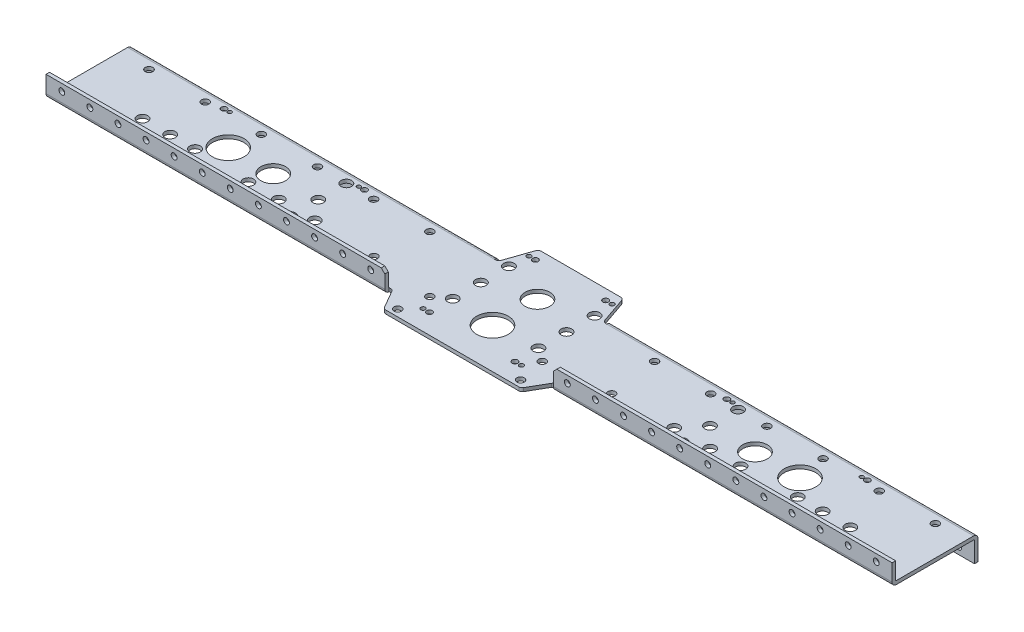
SolidWorks part; units mm, degrees
ref_plane "Front Plane" through (0, 0, 0) normal (0, 0, 1) x (1, 0, 0)
ref_plane "Top Plane" through (0, 0, 0) normal (0, 1, 0) x (1, 0, 0)
ref_plane "Right Plane" through (0, 0, 0) normal (1, 0, 0) x (0, 0, -1)
ref_plane "Plane1" through (0, 3.175, 0) normal (0, 1, 0) x (1, 0, 0)
sketch "Sketch1" plane through (0, 3.175, 0) normal (0, 1, 0) x (1, 0, 0)
  line L0 (457.2, 73.787) -> (457.2, -3.937)
  line L1 (457.2, -3.937) -> (812.8, -3.937)
  line L2 (812.8, -3.937) -> (812.8, 73.787)
  line L3 (812.8, 73.787) -> (457.2, 73.787)
extrude "Boss-Extrude1" add sketch "Sketch1" against normal blind 22.225
sketch "Sketch2" plane through (812.8, 0, 0) normal (1, 0, 0) x (0, 0, -1)
  line L0 (70.612, -19.05) -> (70.612, 0)
  line L1 (70.612, 0) -> (-3.937, 0)
  line L2 (-3.937, 0) -> (-3.937, -19.05)
  line L3 (-3.937, -19.05) -> (70.612, -19.05)
extrude "Cut-Extrude1" cut sketch "Sketch2" against normal through all
sketch "Sketch3" plane through (0, 0, 0) normal (0, -1, 0) x (1, 0, 0)
  line L0 (457.2, 0) -> (482.6, 0)
  line L1 (482.6, 0) -> (482.6, 3.937)
  line L2 (482.6, 3.937) -> (457.2, 3.937)
  line L3 (457.2, 3.937) -> (457.2, 0)
extrude "Cut-Extrude2" cut sketch "Sketch3" against normal through all
sketch "Sketch4" plane through (0, 3.175, 0) normal (0, 1, 0) x (-1, 0, 0)
  line L0 (-812.8, 3.937) -> (-482.6, 3.937)
  line L1 (-482.6, 3.937) -> (-482.6, 0.762)
  line L2 (-482.6, 0.762) -> (-812.8, 0.762)
  line L3 (-812.8, 0.762) -> (-812.8, 3.937)
extrude "Boss-Extrude2" add sketch "Sketch4" along normal blind 15.875
sketch "Sketch5" plane through (457.2, 0, 0) normal (-1, 0, 0) x (0, 0, 1)
  line L0 (0, 3.175) -> (0, 0)
  line L1 (0, 0) -> (-69.85, 0)
  line L2 (-69.85, 0) -> (-69.85, 3.175)
  line L3 (-69.85, 3.175) -> (0, 3.175)
extrude "Boss-Extrude3" add sketch "Sketch5" along normal blind 457.2
sketch "Sketch6" plane through (0, 0, 0) normal (0, 0, 1) x (1, 0, 0)
  line L0 (330.2, 3.175) -> (330.2, 0)
  line L1 (330.2, 0) -> (0, 0)
  line L2 (0, 0) -> (0, 3.175)
  line L3 (0, 3.175) -> (330.2, 3.175)
extrude "Boss-Extrude4" add sketch "Sketch6" along normal blind 3.937
sketch "Sketch7" plane through (0, 3.175, 0) normal (0, 1, 0) x (-1, 0, 0)
  line L0 (-330.2, 3.937) -> (0, 3.937)
  line L1 (0, 3.937) -> (0, 0.762)
  line L2 (0, 0.762) -> (-330.2, 0.762)
  line L3 (-330.2, 0.762) -> (-330.2, 3.937)
extrude "Boss-Extrude5" add sketch "Sketch7" along normal blind 15.875
sketch "Sketch8" plane through (0, 0, -69.85) normal (0, 0, -1) x (-1, 0, 0)
  line L0 (-355.6, 0) -> (-355.6, 3.175)
  line L1 (-355.6, 3.175) -> (0, 3.175)
  line L2 (0, 3.175) -> (0, 0)
  line L3 (0, 0) -> (-355.6, 0)
extrude "Boss-Extrude6" add sketch "Sketch8" along normal blind 3.937
sketch "Sketch9" plane through (0, 0, 0) normal (0, -1, 0) x (1, 0, 0)
  line L0 (0, -70.612) -> (355.6, -70.612)
  line L1 (355.6, -70.612) -> (355.6, -73.787)
  line L2 (355.6, -73.787) -> (0, -73.787)
  line L3 (0, -73.787) -> (0, -70.612)
extrude "Boss-Extrude7" add sketch "Sketch9" along normal blind 19.05
sketch "Sketch10" plane through (0, 0, 0) normal (0, 0, 1) x (1, 0, 0)
  line L0 (344.3735, 3.175) -> (468.4265, 3.175)
  line L1 (468.4265, 3.175) -> (468.4265, 0)
  line L2 (468.4265, 0) -> (344.3735, 0)
  line L3 (344.3735, 0) -> (344.3735, 3.175)
extrude "Boss-Extrude8" add sketch "Sketch10" along normal blind 19.05
sketch "Sketch11" plane through (0, 0, -69.85) normal (0, 0, -1) x (-1, 0, 0)
  line L0 (-444.5794, 3.175) -> (-368.2206, 3.175)
  line L1 (-368.2206, 3.175) -> (-368.2206, 0)
  line L2 (-368.2206, 0) -> (-444.5794, 0)
  line L3 (-444.5794, 0) -> (-444.5794, 3.175)
extrude "Boss-Extrude9" add sketch "Sketch11" along normal blind 27.432
draft "Draft1" type of draft neutral plane draft angle 30 faces to draft 2 face at (344.3735, 1.5875, 9.525) face at (468.4265, 1.5875, 9.525) neutral plane through (0, 0, 19.05) neutral plane normal (0, 0, 1) parameters "D1"=30
draft "Draft2" type of draft neutral plane draft angle 19 faces to draft 2 face at (368.2206, 1.5875, -83.566) face at (444.5794, 1.5875, -83.566) neutral plane through (0, 0, -97.282) neutral plane normal (0, 0, -1) parameters "D1"=19
hole_wizard "#6 Clearance Hole1" positions "Sketch13" profile "Sketch12" hole size "#6" standard "ANSI Inch"
sketch "Sketch13" plane through (0, 0, 0) normal (0, -1, 0) x (-1, 0, 0)
  point P0 (-450.8881, -1.0389)
  point P1 (-361.9119, -1.0389)
  point P2 (-368.808, 87.8535)
  point P3 (-443.992, 87.8535)
sketch "Sketch12" plane through (450.8881, 0, 1.0389) normal (1, 0, 0) x (0, 0, -1)
  line L0 (0, 0) -> (0, 19.05)
  line L1 (0, 19.05) -> (2.032, 19.05)
  line L2 (2.032, 19.05) -> (2.032, 0)
  line L5 (2.032, 0) -> (0, 0)
  line L11 (0, -6.35) -> (0, 107.95) construction
  dimension "Thru Hole Dia." = 4.064
  dimension "Thru Hole Depth" = 19.05
hole_wizard "Hole1" positions "Sketch15" profile "Sketch14" legacy
sketch "Sketch15" plane through (0, 0, 0) normal (0, -1, 0) x (-1, 0, 0)
  point P0 (-147.8292, 36.83)
  point P1 (-406.4, 17.272)
  point P2 (-664.9708, 36.83)
sketch "Sketch14" plane through (147.8292, 0, -36.83) normal (1, 0, 0) x (0, 0, -1)
  line L0 (0, 0) -> (0, 19.05)
  line L1 (0, 19.05) -> (14.2875, 19.05)
  line L2 (14.2875, 19.05) -> (14.2875, 0)
  line L3 (14.2875, 0) -> (0, 0)
  line L4 (0, 110) -> (0, -10) construction
  dimension "Diameter" = 28.575
  dimension "Depth" = 19.05
hole_wizard "7/8 (0.875) Diameter Hole1" positions "Sketch17" profile "Sketch16" hole size "7/8" standard "ANSI Inch"
sketch "Sketch17" plane through (0, 0, 0) normal (0, -1, 0) x (-1, 0, 0)
  point P0 (-188.5454, 36.83)
  point P1 (-406.4, 57.9628)
  point P2 (-624.2546, 36.83)
sketch "Sketch16" plane through (188.5454, 0, -36.83) normal (1, 0, 0) x (0, 0, -1)
  line L0 (0, 0) -> (0, 19.05)
  line L1 (0, 19.05) -> (11.1125, 19.05)
  line L2 (11.1125, 19.05) -> (11.1125, 0)
  line L5 (11.1125, 0) -> (0, 0)
  line L11 (0, -6.35) -> (0, 107.95) construction
  dimension "Thru Hole Dia." = 22.225
  dimension "Thru Hole Depth" = 19.05
hole_wizard "3/8 (0.375) Diameter Hole1" positions "Sketch19" profile "Sketch18" hole size "3/8" standard "ANSI Inch"
sketch "Sketch19" plane through (0, 0, 0) normal (0, -1, 0) x (-1, 0, 0)
  point P0 (-229.2616, 11.43)
  point P1 (-229.2616, 62.23)
  point P2 (-229.2616, 36.83)
  point P3 (-367.6757, 70.866)
  point P4 (-367.6757, 20.066)
  point P5 (-445.1243, 20.066)
  point P6 (-445.1243, 70.866)
  point P7 (-367.6757, 45.466)
  point P8 (-445.1243, 45.466)
  point P9 (-628.9477, 19.05)
  point P10 (-601.4385, 19.05)
  point P11 (-568.9249, 19.05)
  point P12 (-243.8751, 19.05)
  point P13 (-211.3615, 19.05)
  point P14 (-183.8523, 19.05)
  point P15 (-678.9442, 20.828)
  point P16 (-701.4504, 20.828)
  point P17 (-726.4609, 20.828)
  point P18 (-133.8558, 20.828)
  point P19 (-111.3496, 20.828)
  point P20 (-86.3391, 20.828)
  point P21 (-583.5384, 62.23)
  point P22 (-583.5384, 36.83)
  point P23 (-583.5384, 11.43)
sketch "Sketch18" plane through (229.2616, 0, -11.43) normal (1, 0, 0) x (0, 0, -1)
  line L0 (0, 0) -> (0, 19.05)
  line L1 (0, 19.05) -> (4.7625, 19.05)
  line L2 (4.7625, 19.05) -> (4.7625, 0)
  line L5 (4.7625, 0) -> (0, 0)
  line L11 (0, -6.35) -> (0, 107.95) construction
  dimension "Thru Hole Dia." = 9.525
  dimension "Thru Hole Depth" = 19.05
hole_wizard "#5 Clearance Hole1" positions "Sketch21" profile "Sketch20" hole size "#5" standard "ANSI Inch"
sketch "Sketch21" plane through (0, 0, 0) normal (0, -1, 0) x (-1, 0, 0)
  point P0 (-237.4404, 65.405)
  point P1 (-237.4404, 8.255)
  point P2 (-120.6004, 8.255)
  point P3 (-120.6004, 65.405)
  point P4 (-575.3596, 65.405)
  point P5 (-575.3596, 8.255)
  point P6 (-692.1996, 65.405)
  point P7 (-692.1996, 8.255)
sketch "Sketch20" plane through (237.4404, 0, -65.405) normal (1, 0, 0) x (0, 0, -1)
  line L0 (0, 0) -> (0, 19.05)
  line L1 (0, 19.05) -> (1.7859, 19.05)
  line L2 (1.7859, 19.05) -> (1.7859, 0)
  line L5 (1.7859, 0) -> (0, 0)
  line L11 (0, -6.35) -> (0, 107.95) construction
  dimension "Thru Hole Dia." = 3.5719
  dimension "Thru Hole Depth" = 19.05
hole_wizard "#7 (0.201) Diameter Hole1" positions "Sketch23" profile "Sketch22" hole size "#7" standard "ANSI Inch"
sketch "Sketch23" plane through (0, 0, 0) normal (0, -1, 0) x (-1, 0, 0)
  point P0 (-242.5204, 65.405)
  point P1 (-242.5204, 8.255)
  point P2 (-115.5204, 8.255)
  point P3 (-115.5204, 65.405)
  point P4 (-367.7539, -1.0389)
  point P5 (-445.0461, -1.0389)
  point P6 (-374.65, 87.8535)
  point P7 (-438.15, 87.8535)
  point P8 (-570.2796, 65.405)
  point P9 (-570.2796, 8.255)
  point P10 (-697.2796, 65.405)
  point P11 (-697.2796, 8.255)
sketch "Sketch22" plane through (242.5204, 0, -65.405) normal (1, 0, 0) x (0, 0, -1)
  line L0 (0, 0) -> (0, 19.05)
  line L1 (0, 19.05) -> (2.5527, 19.05)
  line L2 (2.5527, 19.05) -> (2.5527, 0)
  line L5 (2.5527, 0) -> (0, 0)
  line L11 (0, -6.35) -> (0, 107.95) construction
  dimension "Thru Hole Dia." = 5.1054
  dimension "Thru Hole Depth" = 19.05
hole_wizard "H (0.266) Diameter Hole1" positions "Sketch25" profile "Sketch24" hole size "H" standard "ANSI Inch"
sketch "Sketch25" plane through (0, 0, 0) normal (0, -1, 0) x (-1, 0, 0)
  point P0 (-508, 62.23)
  point P1 (-558.8, 11.43)
  point P2 (-558.8, 62.23)
  point P3 (-609.6, 11.43)
  point P4 (-457.2, 11.43)
  point P5 (-355.6, 11.43)
  point P6 (-304.8, 62.23)
  point P7 (-254, 62.23)
  point P8 (-152.4, 11.43)
  point P9 (-101.6, 62.23)
  point P10 (-101.6, 11.43)
  point P11 (-50.8, 62.23)
  point P12 (-254, 11.43)
  point P13 (-203.2, 62.23)
  point P14 (-203.2, 11.43)
  point P15 (-152.4, 62.23)
  point P16 (-711.2, 62.23)
  point P17 (-762, 11.43)
  point P18 (-762, 62.23)
  point P19 (-609.6, 62.23)
  point P20 (-660.4, 11.43)
  point P21 (-660.4, 62.23)
  point P22 (-711.2, 11.43)
  point P23 (-50.8, 11.43)
  point P24 (-461.9625, -12.8905)
  point P25 (-350.8375, -12.8905)
  point P26 (-513.9255, 17.5473)
  point P27 (-298.8745, 17.5473)
sketch "Sketch24" plane through (508, 0, -62.23) normal (1, 0, 0) x (0, 0, -1)
  line L0 (0, 0) -> (0, 19.05)
  line L1 (0, 19.05) -> (3.3782, 19.05)
  line L2 (3.3782, 19.05) -> (3.3782, 0)
  line L5 (3.3782, 0) -> (0, 0)
  line L11 (0, -6.35) -> (0, 107.95) construction
  dimension "Thru Hole Dia." = 6.7564
  dimension "Thru Hole Depth" = 19.05
hole_wizard "#10 Clearance Hole1" positions "Sketch27" profile "Sketch26" hole size "#10" standard "ANSI Inch"
sketch "Sketch27" plane through (0, 0, 3.937) normal (0, 0, 1) x (1, 0, 0)
  point P0 (495.3, 12.7)
  point P1 (520.7, 12.7)
  point P2 (546.1, 12.7)
  point P3 (571.5, 12.7)
  point P4 (596.9, 12.7)
  point P5 (622.3, 12.7)
  point P6 (647.7, 12.7)
  point P7 (673.1, 12.7)
  point P8 (698.5, 12.7)
  point P9 (723.9, 12.7)
  point P10 (749.3, 12.7)
  point P11 (774.7, 12.7)
  point P12 (800.1, 12.7)
  point P13 (317.5, 12.7)
  point P14 (292.1, 12.7)
  point P15 (266.7, 12.7)
  point P16 (241.3, 12.7)
  point P17 (215.9, 12.7)
  point P18 (190.5, 12.7)
  point P19 (165.1, 12.7)
  point P20 (139.7, 12.7)
  point P21 (114.3, 12.7)
  point P22 (88.9, 12.7)
  point P23 (63.5, 12.7)
  point P24 (12.7, 12.7)
  point P25 (38.1, 12.7)
sketch "Sketch26" plane through (495.3, 12.7, 3.937) normal (1, 0, 0) x (0, -1, 0)
  line L0 (0, 0) -> (0, 101.219)
  line L1 (0, 101.219) -> (2.667, 101.219)
  line L2 (2.667, 101.219) -> (2.667, 0)
  line L5 (2.667, 0) -> (0, 0)
  line L11 (0, -6.35) -> (0, 107.95) construction
  dimension "Thru Hole Dia." = 5.334
  dimension "Thru Hole Depth" = 101.219
hole_wizard "#10 Clearance Hole2" positions "Sketch29" profile "Sketch28" hole size "#10" standard "ANSI Inch"
sketch "Sketch29" plane through (0, 0, -70.612) normal (0, 0, 1) x (1, 0, 0)
  point P0 (469.9, -12.7)
  point P1 (495.3, -12.7)
  point P2 (520.7, -12.7)
  point P3 (546.1, -12.7)
  point P4 (571.5, -12.7)
  point P5 (596.9, -12.7)
  point P6 (622.3, -12.7)
  point P7 (647.7, -12.7)
  point P8 (673.1, -12.7)
  point P9 (698.5, -12.7)
  point P10 (723.9, -12.7)
  point P11 (749.3, -12.7)
  point P12 (774.7, -12.7)
  point P13 (800.1, -12.7)
  point P14 (342.9, -12.7)
  point P15 (317.5, -12.7)
  point P16 (292.1, -12.7)
  point P17 (266.7, -12.7)
  point P18 (241.3, -12.7)
  point P19 (215.9, -12.7)
  point P20 (190.5, -12.7)
  point P21 (165.1, -12.7)
  point P22 (139.7, -12.7)
  point P23 (114.3, -12.7)
  point P24 (88.9, -12.7)
  point P25 (63.5, -12.7)
  point P26 (38.1, -12.7)
  point P27 (12.7, -12.7)
sketch "Sketch28" plane through (469.9, -12.7, -70.612) normal (1, 0, 0) x (0, -1, 0)
  line L0 (0, 0) -> (0, 26.67)
  line L1 (0, 26.67) -> (2.667, 26.67)
  line L2 (2.667, 26.67) -> (2.667, 0)
  line L5 (2.667, 0) -> (0, 0)
  line L11 (0, -6.35) -> (0, 107.95) construction
  dimension "Thru Hole Dia." = 5.334
  dimension "Thru Hole Depth" = 26.67
chamfer "Chamfer1" distance 3.175 angle 45 8 edges at (0, -19.05, -72.1995) (0, 19.05, 2.3495) (330.2, 19.05, 2.3495) (812.8, 19.05, 2.3495) (355.6, -19.05, -72.1995) (482.6, 19.05, 2.3495) (812.8, -19.05, -72.1995) (457.2, -19.05, -72.1995)
fillet "Fillet1" radius 0.762 4 edges at (635, 0, -70.612) (165.1, 3.175, 0.762) (647.7, 3.175, 0.762) (177.8, 0, -70.612)
fillet "Fillet2" radius 3.175 8 edges at (344.3735, 1.5875, 19.05) (454.025, 1.5875, -69.85) (333.375, 1.5875, 0) (368.2206, 1.5875, -97.282) (358.775, 1.5875, -69.85) (468.4265, 1.5875, 19.05) (444.5794, 1.5875, -97.282) (479.425, 1.5875, 0)
fillet "Fillet3" radius 3.937 4 edges at (177.8, 3.175, -73.787) (165.1, 0, 3.937) (647.7, 0, 3.937) (635, 3.175, -73.787)
sketch "Sketch30" plane through (0, 0, 0) normal (0, -1, 0) x (-1, 0, 0)
  line L0 (-809.625, 73.787) -> (-460.375, 73.787) construction
  line L1 (0, 73.787) -> (-23.8125, 73.787)
  line L2 (0, 73.787) -> (0, -3.937)
  line L3 (0, -3.937) -> (-23.8125, -3.937)
  line L4 (-23.8125, 73.787) -> (-23.8125, -3.937)
  line L5 (-812.8, -3.937) -> (-788.9875, -3.937)
  line L6 (-812.8, -3.937) -> (-812.8, 73.787)
  line L7 (-812.8, 73.787) -> (-788.9875, 73.787)
  line L8 (-788.9875, -3.937) -> (-788.9875, 73.787)
  line L9 (0, -3.937) -> (-330.2, -3.937) construction
  point P11 (0, 0)
  point P12 (-777.367, 78.8439)
  point P15 (0, 0)
  point P16 (-46.7039, -3.937)
  dimension "D1" = 765.175
extrude "Cut-Extrude3" cut sketch "Sketch30" against normal up to next and the other way up to next
